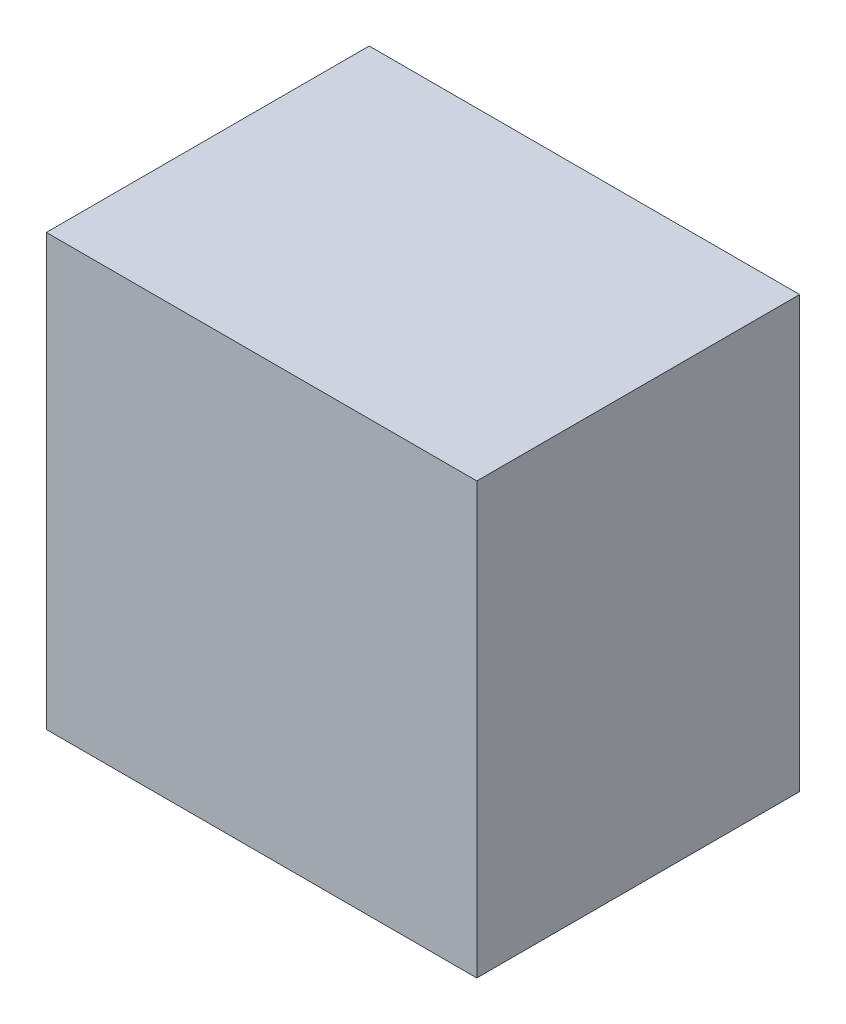
SolidWorks part; units mm, degrees
ref_plane "Front Plane" through (0, 0, 0) normal (0, 0, 1) x (1, 0, 0)
ref_plane "Top Plane" through (0, 0, 0) normal (0, 1, 0) x (1, 0, 0)
ref_plane "Right Plane" through (0, 0, 0) normal (1, 0, 0) x (0, 0, -1)
sketch "Sketch1" plane through (0, 0, 0) normal (0, 1, 0) x (1, 0, 0)
  line L1 (-1000, 750) -> (1000, 750)
  line L2 (-1000, 750) -> (-1000, -750)
  line L3 (-1000, -750) -> (1000, -750)
  line L4 (1000, 750) -> (1000, -750)
  line L5 (0, -750) -> (0, 750) construction
  line L6 (-1000, 0) -> (1000, 0) construction
  point P4 (0, 0)
  point P264 (0, 0)
  dimension "D1" = 2000
  dimension "D2" = 1500
extrude "Boss-Extrude1" add sketch "Sketch1" along normal blind 2000
